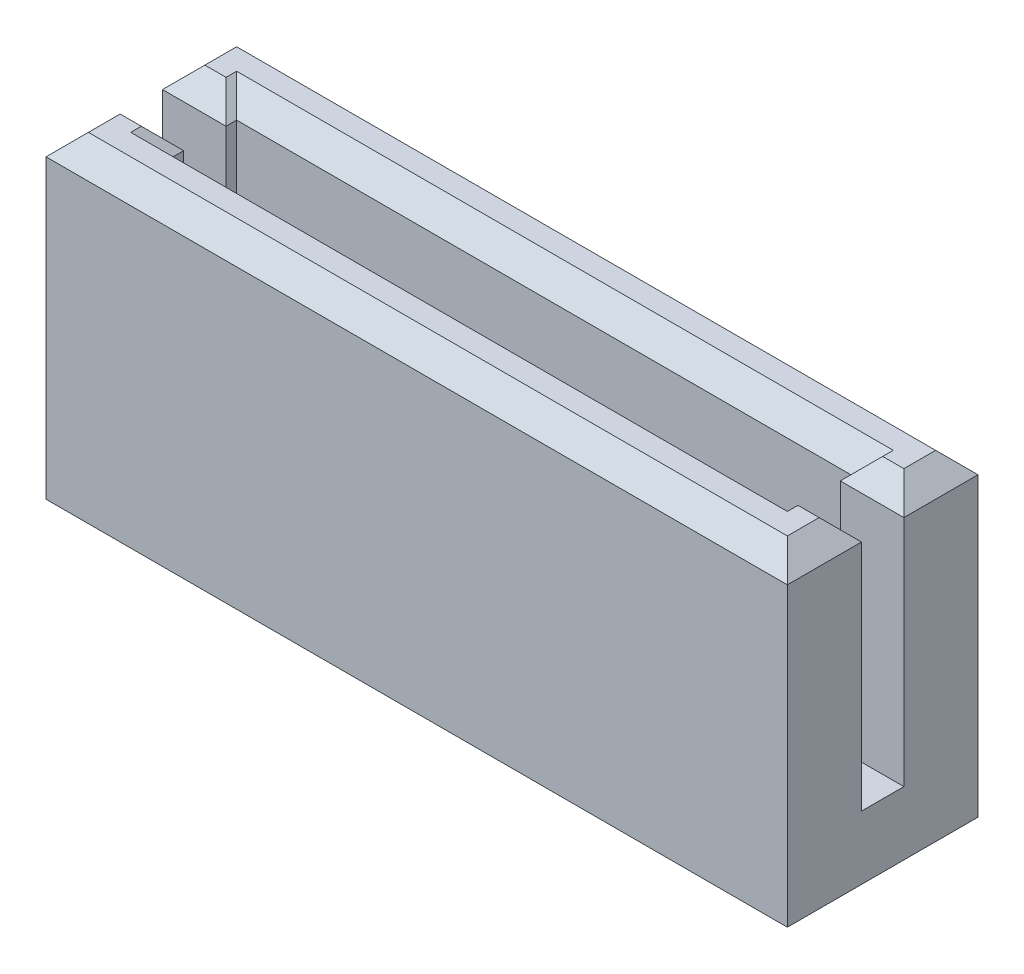
SolidWorks part; units mm, degrees
ref_plane "Front Plane" through (0, 0, 0) normal (0, 0, 1) x (1, 0, 0)
ref_plane "Top Plane" through (0, 0, 0) normal (0, 1, 0) x (1, 0, 0)
ref_plane "Right Plane" through (0, 0, 0) normal (1, 0, 0) x (0, 0, -1)
sketch "Sketch1" plane through (0, 0, 0) normal (0, 1, 0) x (1, 0, 0)
  line L1 (0, 0) -> (35, 0)
  line L2 (0, 0) -> (0, 9)
  line L3 (0, 9) -> (35, 9)
  line L4 (35, 0) -> (35, 9)
  dimension "D1" = 35
  dimension "D2" = 9
extrude "Boss-Extrude1" add sketch "Sketch1" along normal blind 3
sketch "Sketch2" plane through (0, 3, 0) normal (0, 1, 0) x (1, 0, 0)
  line L0 (35, 0) -> (35, 9) construction
  line L1 (0, 9) -> (35, 9)
  line L2 (0, 9) -> (0, 6.8131)
  line L3 (3, 6) -> (32, 6)
  line L4 (35, 9) -> (35, 6)
  line L5 (0, 9) -> (0, 0) construction
  line L6 (0, 0) -> (35, 0)
  line L7 (0, 0) -> (0, 2.1869)
  line L8 (3, 3) -> (32, 3)
  line L9 (35, 0) -> (35, 3)
  line L11 (0, 6.8131) -> (0, 5.5)
  line L12 (0, 5.5) -> (3, 5.5)
  line L13 (3, 6) -> (3, 5.5)
  line L15 (0, 2.1869) -> (0, 3.5)
  line L16 (0, 3.5) -> (3, 3.5)
  line L17 (3, 3) -> (3, 3.5)
  line L20 (35, 6) -> (35, 5.5)
  line L21 (35, 5.5) -> (32, 5.5)
  line L22 (32, 6) -> (32, 5.5)
  line L24 (35, 3) -> (35, 3.5)
  line L25 (35, 3.5) -> (32, 3.5)
  line L26 (32, 3) -> (32, 3.5)
  point P18 (3, 3.25)
  dimension "D1" = 3
  dimension "D2" = 3
  dimension "D3" = 3
  dimension "D4" = 2
extrude "Boss-Extrude2" add sketch "Sketch2" along normal blind 12
chamfer "Chamfer1" distance 1 angle 45 16 edges at (17.5, 15, -9) (35, 15, -7.25) (33.5, 15, -5.5) (32, 15, -5.75) (17.5, 15, -6) (3, 15, -5.75) (1.5, 15, -5.5) (0, 15, -7.25) (1.5, 15, -3.5) (3, 15, -3.25) (17.5, 15, -3) (32, 15, -3.25) (33.5, 15, -3.5) (35, 15, -1.75) (17.5, 15, 0) (0, 15, -1.75)
